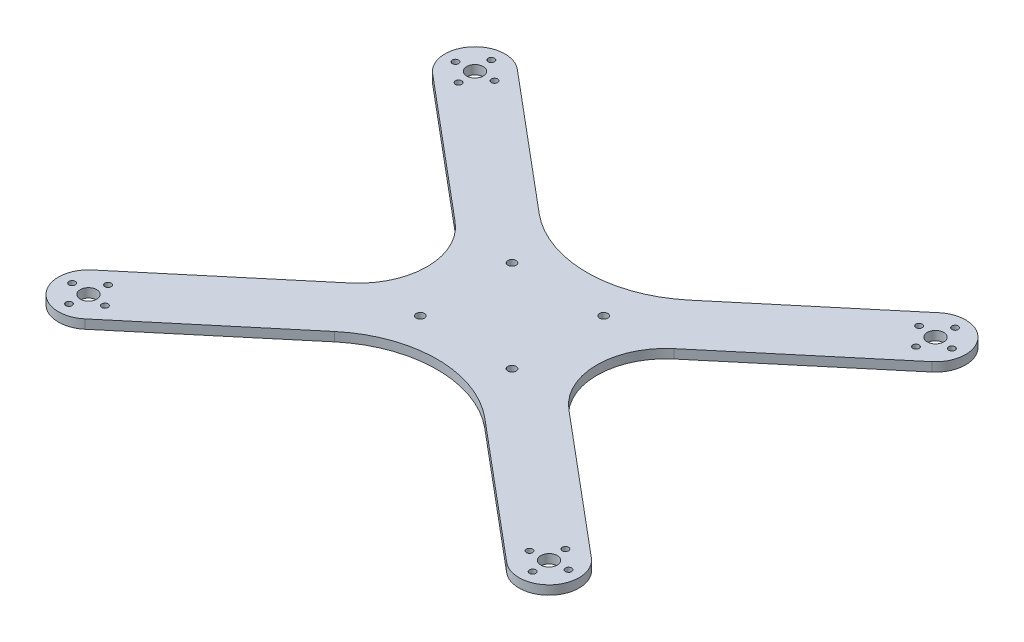
SolidWorks part; units mm, degrees
material "Custom Plastic"
ref_plane "Front Plane" through (0, 0, 0) normal (0, 0, 1) x (1, 0, 0)
ref_plane "Top Plane" through (0, 0, 0) normal (0, 1, 0) x (1, 0, 0)
ref_plane "Right Plane" through (0, 0, 0) normal (1, 0, 0) x (0, 0, -1)
sketch "Sketch1" plane through (0, 0, 0) normal (0, 1, 0) x (1, 0, 0)
  line L1 (-36.375, -26.375) -> (36.375, -26.375) construction
  line L2 (-36.375, -26.375) -> (-36.375, 26.375) construction
  line L3 (-36.375, 26.375) -> (36.375, 26.375) construction
  line L4 (36.375, -26.375) -> (36.375, 26.375) construction
  line L5 (-36.375, -26.375) -> (36.375, 26.375) construction
  line L6 (-36.375, 26.375) -> (36.375, -26.375) construction
  circle A0 centre (-36.375, 26.375) radius 1.25
  circle A4 centre (36.375, 26.375) radius 1.25
  circle A5 centre (36.375, -26.375) radius 1.25
  circle A6 centre (-36.375, -26.375) radius 1.25
  point P8 (0, 0)
  dimension "D1" = 2.5
  dimension "D2" = 52.75
  dimension "D3" = 72.75
sketch "Sketch2" plane through (0, 0, 0) normal (0, 1, 0) x (1, 0, 0)
  line L0 (0, 0) -> (-76.6044, 64.2788) construction
  line L1 (0, 0) -> (76.6044, 64.2788) construction
  line L2 (0, 0) -> (76.6044, -64.2788) construction
  line L3 (0, 0) -> (-76.6044, -64.2788) construction
  line L4 (-30, 0) -> (30, 0) construction
  line L5 (-70.1766, 71.9392) -> (-83.0323, 56.6183) construction
  line L10 (36.4129, -30.5541) -> (-32.6921, 27.4319) construction
  line L12 (0, 21.0062) -> (0, -21.0062) construction
  line L13 (-83.0323, 56.6183) -> (-36.4129, 17.5)
  line L14 (83.0323, -56.6183) -> (36.4129, -17.5)
  line L15 (-82.5816, 63.7558) -> (-70.6273, 64.8017) construction
  line L16 (-77.1274, 70.2559) -> (-76.0815, 58.3016) construction
  line L17 (-83.0323, -56.6183) -> (-70.1766, -71.9392) construction
  line L18 (-83.0323, -56.6183) -> (-36.4129, -17.5)
  line L19 (-70.1766, -71.9392) -> (-25, -34.0316)
  line L21 (25, 34.0316) -> (70.1766, 71.9392)
  line L22 (-25, 34.0316) -> (-70.1766, 71.9392)
  line L23 (36.4129, 17.5) -> (83.0323, 56.6183)
  line L24 (25, -34.0316) -> (70.1766, -71.9392)
  arc A3 (-70.1766, 71.9392) -> (-83.0323, 56.6183) centre (-76.6044, 64.2788) ccw
  circle A4 centre (-77.1274, 70.2559) radius 1.05
  circle A5 centre (-70.6273, 64.8017) radius 1.05
  circle A6 centre (-76.0815, 58.3016) radius 1.05
  circle A7 centre (-82.5816, 63.7558) radius 1.05
  circle A8 centre (-76.6044, 64.2788) radius 2.75
  circle A9 centre (-77.1274, -70.2559) radius 1.05
  circle A10 centre (-76.0815, -58.3016) radius 1.05
  circle A11 centre (-82.5816, -63.7558) radius 1.05
  circle A12 centre (-76.6044, -64.2788) radius 2.75
  circle A13 centre (-70.6273, -64.8017) radius 1.05
  arc A14 (-70.1766, -71.9392) -> (-83.0323, -56.6183) centre (-76.6044, -64.2788) cw
  arc A15 (70.1766, -71.9392) -> (83.0323, -56.6183) centre (76.6044, -64.2788) ccw
  circle A16 centre (70.6273, -64.8017) radius 1.05
  circle A17 centre (76.6044, -64.2788) radius 2.75
  circle A18 centre (82.5816, -63.7558) radius 1.05
  circle A19 centre (76.0815, -58.3016) radius 1.05
  circle A20 centre (77.1274, -70.2559) radius 1.05
  circle A21 centre (76.6044, 64.2788) radius 2.75
  circle A22 centre (82.5816, 63.7558) radius 1.05
  circle A23 centre (76.0815, 58.3016) radius 1.05
  circle A24 centre (70.6273, 64.8017) radius 1.05
  circle A25 centre (77.1274, 70.2559) radius 1.05
  arc A26 (70.1766, 71.9392) -> (83.0323, 56.6183) centre (76.6044, 64.2788) cw
  arc A27 (-36.4129, 17.5) -> (-36.4129, -17.5) centre (-51.0972, 0) cw
  arc A28 (-25, -34.0316) -> (25, -34.0316) centre (0, -63.8254) cw
  arc A29 (36.4129, -17.5) -> (36.4129, 17.5) centre (51.0972, 0) cw
  arc A30 (25, 34.0316) -> (-25, 34.0316) centre (0, 63.8254) cw
  point P29 (-76.6044, 64.2788)
  point P34 (-76.6044, 64.2788)
  point P35 (-76.6044, 64.2788)
  point P61 (76.6044, 64.2788)
  point P63 (0, 0)
  dimension "D5" = 20
  dimension "D7" = 2.1
  dimension "D10" = 5.5
  dimension "D2" = 50
  dimension "D3" = 40
  dimension "D4" = 100
  dimension "D6" = 35
  dimension "D8" = 12
  dimension "D9" = 45
extrude "Boss-Extrude2" add sketch "Sketch2" along normal blind 3
sketch "Sketch4" plane through (0, 0, 0) normal (0, 1, 0) x (1, 0, 0)
  line L1 (-15.25, -15.25) -> (15.25, -15.25) construction
  line L2 (-15.25, -15.25) -> (-15.25, 15.25) construction
  line L3 (-15.25, 15.25) -> (15.25, 15.25) construction
  line L4 (15.25, -15.25) -> (15.25, 15.25) construction
  line L5 (-15.25, -15.25) -> (15.25, 15.25) construction
  line L6 (-15.25, 15.25) -> (15.25, -15.25) construction
  circle A0 centre (-15.25, 15.25) radius 1.375
  circle A1 centre (15.25, -15.25) radius 1.375
  circle A2 centre (-15.25, -15.25) radius 1.375
  circle A3 centre (15.25, 15.25) radius 1.375
  point P5 (0, 0)
  dimension "D2" = 2.75
  dimension "D1" = 30.5
extrude "Cut-Extrude1" cut sketch "Sketch4" along normal blind 3
